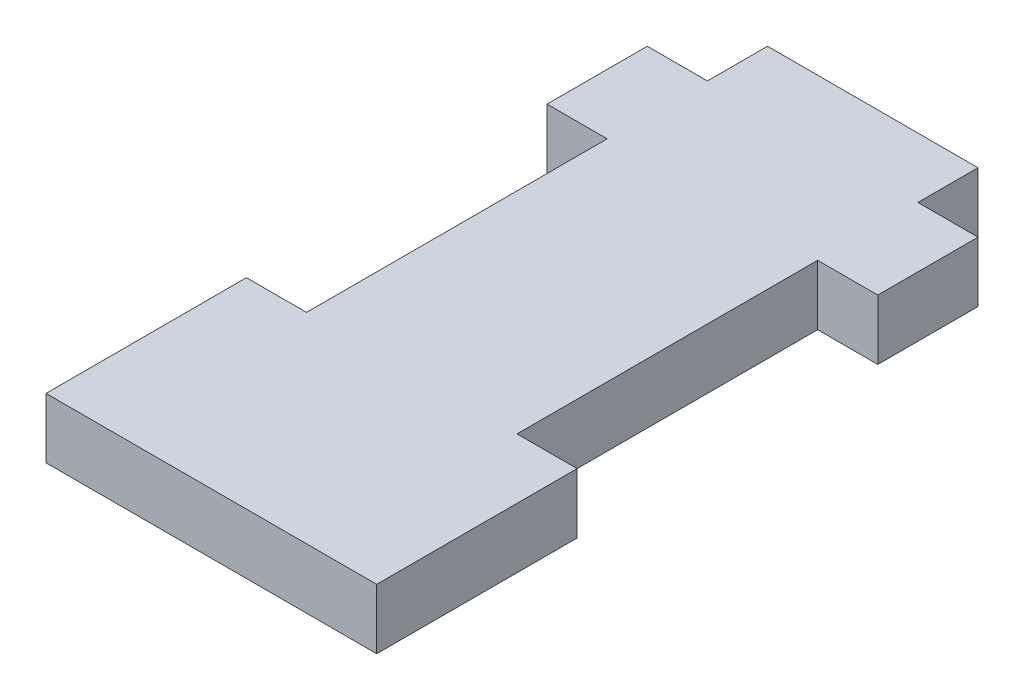
SolidWorks part; units mm, degrees
ref_plane "前视基准面" through (0, 0, 0) normal (0, 0, 1) x (1, 0, 0)
ref_plane "上视基准面" through (0, 0, 0) normal (0, 1, 0) x (1, 0, 0)
ref_plane "右视基准面" through (0, 0, 0) normal (1, 0, 0) x (0, 0, -1)
other "Configuration Table"
sketch "草图1" plane through (0, 0, 0) normal (0, 1, 0) x (1, 0, 0)
  line L3 (0, -55) -> (10.5, -55)
  line L21 (10.5, -45) -> (13.5, -45)
  line L22 (0, -55) -> (-3, -55)
  line L23 (0, -55) -> (0, -45)
  line L24 (0, -45) -> (-3, -45)
  line L25 (-3, -55) -> (-3, -45)
  line L26 (0, -30) -> (-3, -30)
  line L27 (0, -30) -> (0, -25)
  line L28 (0, -25) -> (-3, -25)
  line L29 (-3, -30) -> (-3, -25)
  line L30 (13.5, -55) -> (13.5, -45)
  line L31 (10.5, -55) -> (13.5, -55)
  line L32 (10.5, -55) -> (10.5, -45)
  line L33 (10.5, -25) -> (13.5, -25)
  line L34 (13.5, -30) -> (13.5, -25)
  line L35 (10.5, -30) -> (13.5, -30)
  line L36 (10.5, -30) -> (10.5, -25)
  line L37 (0, -22) -> (10.5, -22)
  line L38 (0, -22) -> (10.5, -22)
  line L39 (0, -22) -> (0, -55)
  line L40 (0, -55) -> (10.5, -55)
  line L41 (10.5, -22) -> (10.5, -55)
  dimension "D2" = 10.5
  dimension "D4" = 3
  dimension "D5" = 3
  dimension "D6" = 10
  dimension "D7" = 5
  dimension "D8" = 15
  dimension "D9" = 3
extrude "凸台-拉伸1" add sketch "草图1" along normal blind 3 contours L41 L37 L39 L27 L23 L3 L32 L36 | L32 L31 L30 L21 | L25 L22 L23 L24 | L29 L26 L27 L28 | L36 L35 L34 L33
